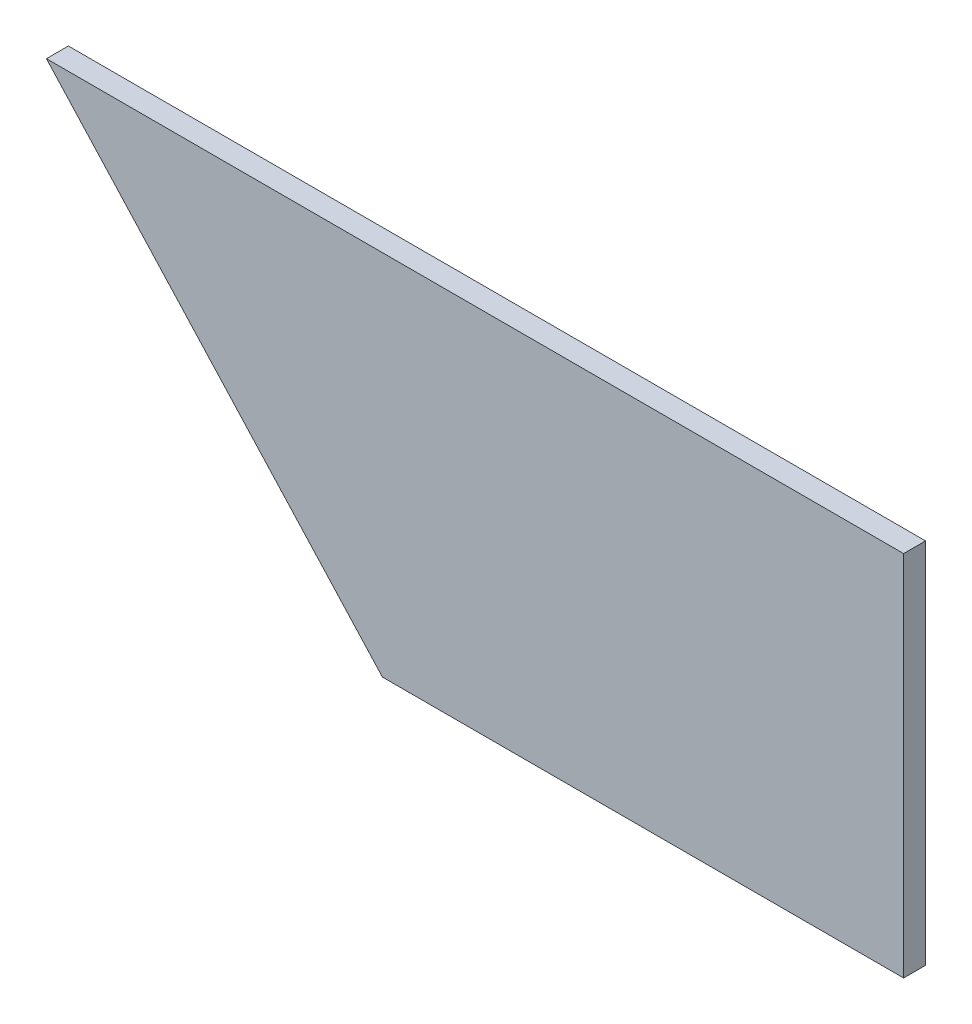
SolidWorks part; units mm, degrees
material "普通碳钢"
ref_plane "前视基准面" through (0, 0, 0) normal (0, 0, 1) x (1, 0, 0)
ref_plane "上视基准面" through (0, 0, 0) normal (0, 1, 0) x (1, 0, 0)
ref_plane "右视基准面" through (0, 0, 0) normal (1, 0, 0) x (0, 0, -1)
sketch "草图1" plane through (0, 0, 0) normal (0, 0, 1) x (1, 0, 0)
  line L0 (0, 0) -> (380, 0)
  line L5 (380, 0) -> (380, 268)
  line L6 (380, 268) -> (-245, 268)
  line L7 (-245, 268) -> (0, 0)
  dimension "D1" = 380
  dimension "D2" = 268
  dimension "D3" = 625
extrude "凸台-拉伸1" add sketch "草图1" along normal blind 16
